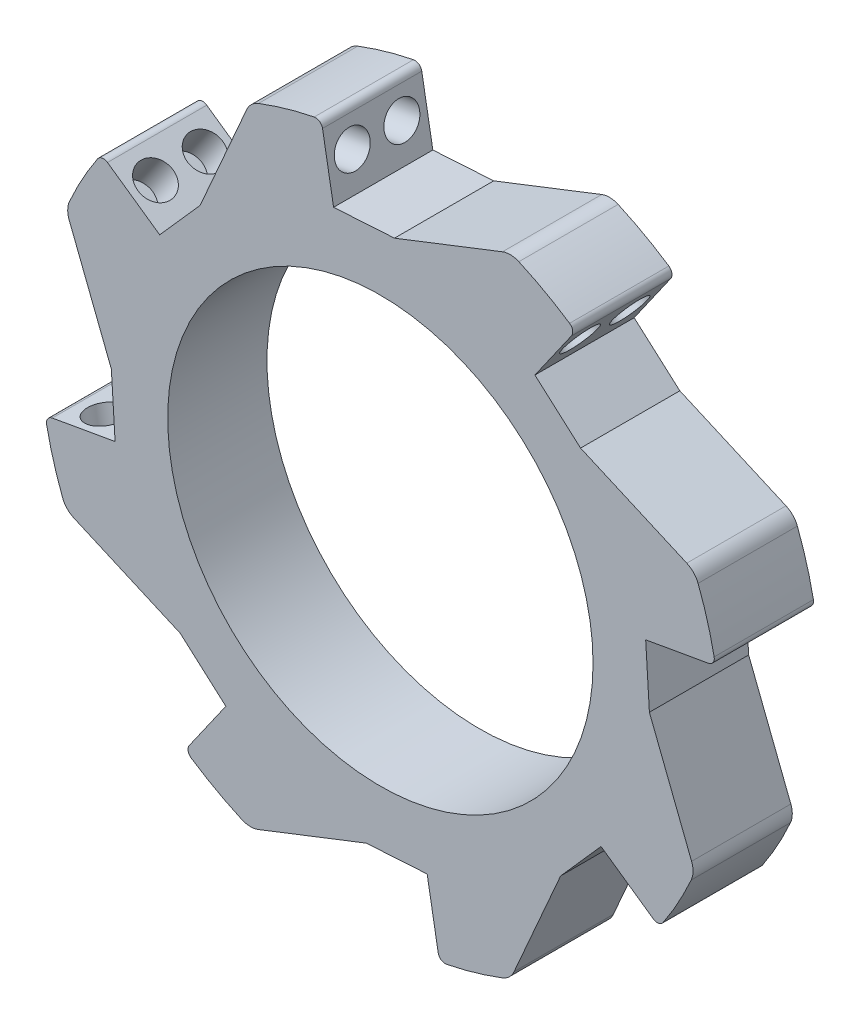
SolidWorks part; units mm, degrees
material "Plain Carbon Steel"
ref_plane "Front Plane" through (0, 0, 0) normal (0, 0, 1) x (1, 0, 0)
ref_plane "Top Plane" through (0, 0, 0) normal (0, 1, 0) x (1, 0, 0)
ref_plane "Right Plane" through (0, 0, 0) normal (1, 0, 0) x (0, 0, -1)
sketch "Sketch1" plane through (0, 0, 0) normal (0, 0, 1) x (1, 0, 0)
  line L0 (0, 48) -> (0, -48) construction
  line L1 (-48, 0) -> (48, 0) construction
  line L2 (-33.9411, -33.9411) -> (33.9411, 33.9411) construction
  line L3 (-33.9411, 33.9411) -> (33.9411, -33.9411) construction
  line L4 (-8.3351, 47.2708) -> (-6.5986, 37.4227)
  line L5 (0, 0) -> (-18.3688, 44.3462) construction
  line L6 (0, 0) -> (-25.427, 28.2395) construction
  line L7 (-25.427, 28.2395) -> (-18.3688, 44.3462)
  line L8 (1.9888, 37.9479) -> (18.3688, 44.3462)
  line L9 (27.5317, 39.3193) -> (21.7959, 31.1278)
  line L10 (28.2395, 25.427) -> (44.3462, 18.3688)
  line L11 (47.2708, 8.3351) -> (37.4227, 6.5986)
  line L12 (37.9479, -1.9888) -> (44.3462, -18.3688)
  line L13 (39.3193, -27.5317) -> (31.1278, -21.7959)
  line L14 (25.427, -28.2395) -> (18.3688, -44.3462)
  line L15 (8.3351, -47.2708) -> (6.5986, -37.4227)
  line L16 (-1.9888, -37.9479) -> (-18.3688, -44.3462)
  line L17 (-27.5317, -39.3193) -> (-21.7959, -31.1278)
  line L18 (-28.2395, -25.427) -> (-44.3462, -18.3688)
  line L19 (-47.2708, -8.3351) -> (-37.4227, -6.5986)
  line L20 (-37.9479, 1.9888) -> (-44.3462, 18.3688)
  line L21 (-39.3193, 27.5317) -> (-31.1278, 21.7959)
  line L22 (-6.5986, 37.4227) -> (1.9888, 37.9479)
  line L23 (21.7959, 31.1278) -> (28.2395, 25.427)
  line L24 (37.4227, 6.5986) -> (37.9479, -1.9888)
  line L25 (31.1278, -21.7959) -> (25.427, -28.2395)
  line L26 (6.5986, -37.4227) -> (-1.9888, -37.9479)
  line L27 (-21.7959, -31.1278) -> (-28.2395, -25.427)
  line L28 (-37.4227, -6.5986) -> (-37.9479, 1.9888)
  line L29 (-31.1278, 21.7959) -> (-25.427, 28.2395)
  circle A0 centre (0, 0) radius 35
  circle A1 centre (0, 0) radius 30
  circle A3 centre (0, 0) radius 48
  circle A4 centre (0, 43) radius 5 construction
  circle A5 centre (30.4056, 30.4056) radius 5 construction
  circle A6 centre (43, 0) radius 5 construction
  circle A7 centre (30.4056, -30.4056) radius 5 construction
  circle A8 centre (0, -43) radius 5 construction
  circle A9 centre (-30.4056, -30.4056) radius 5 construction
  circle A10 centre (-43, 0) radius 5 construction
  circle A11 centre (-30.4056, 30.4056) radius 5 construction
  point P32 (0, 0)
  point P65 (0, 0)
  point P79 (0, 0)
  dimension "D1" = 60
  dimension "D2" = 70
  dimension "D3" = 96
  dimension "D4" = 8
  dimension "D7" = 10
  dimension "D5" = 45
  dimension "D6" = 45
  dimension "D8" = 43
  dimension "D10" = 10
  dimension "D11" = 22.5
  dimension "D12" = 3
  dimension "D13" = 10
  dimension "D14" = 38
  dimension "D9" = 8
  dimension "D15" = 8
extrude "Boss-Extrude2" add sketch "Sketch1" along normal blind 14 contours A0 A1 | L11 A3 L10 L23 L9 L8 L22 L4 L7 L29 L21 L20 L28 L19 L18 L27 L17 L16 L26 L15 L14 L25 L13 L12 L24 A0
fillet "Fillet1" radius 3 1 edges at (-18.3688, 44.3462, 7)
fillet "Fillet2" radius 3 7 edges at (18.3688, 44.3462, 7) (44.3462, 18.3688, 7) (44.3462, -18.3688, 7) (18.3688, -44.3462, 7) (-18.3688, -44.3462, 7) (-44.3462, -18.3688, 7) (-44.3462, 18.3688, 7)
fillet "Fillet3" radius 1 8 edges at (39.3193, -27.5317, 7) (8.3351, -47.2708, 7) (-27.5317, -39.3193, 7) (47.2708, 8.3351, 7) (27.5317, 39.3193, 7) (-8.3351, 47.2708, 7) (-39.3193, 27.5317, 7) (-47.2708, -8.3351, 7)
sketch "Sketch2" plane through (0, 0, 0) normal (0.8192, -0.5736, 0) x (0, 0, -1)
  line L0 (-14, 38) -> (0, 38) construction
  line L1 (-14, 46.9894) -> (-14, 38) construction
  line L2 (0, 46.9894) -> (0, 38) construction
  circle A0 centre (-10.5, 43) radius 2.5
  circle A1 centre (-3.5, 43) radius 2.5
  dimension "D1" = 5
  dimension "D2" = 5
  dimension "D3" = 5
  dimension "D4" = 3.5
  dimension "D5" = 3.5
  dimension "D6" = 5
extrude "Cut-Extrude1" cut sketch "Sketch2" against normal blind 5 contours A1 | A0
pattern_circular "CirPattern3" count 8 over 360 about axis through (0, 0, 0) along (0, 0, 1) of "Cut-Extrude1"
